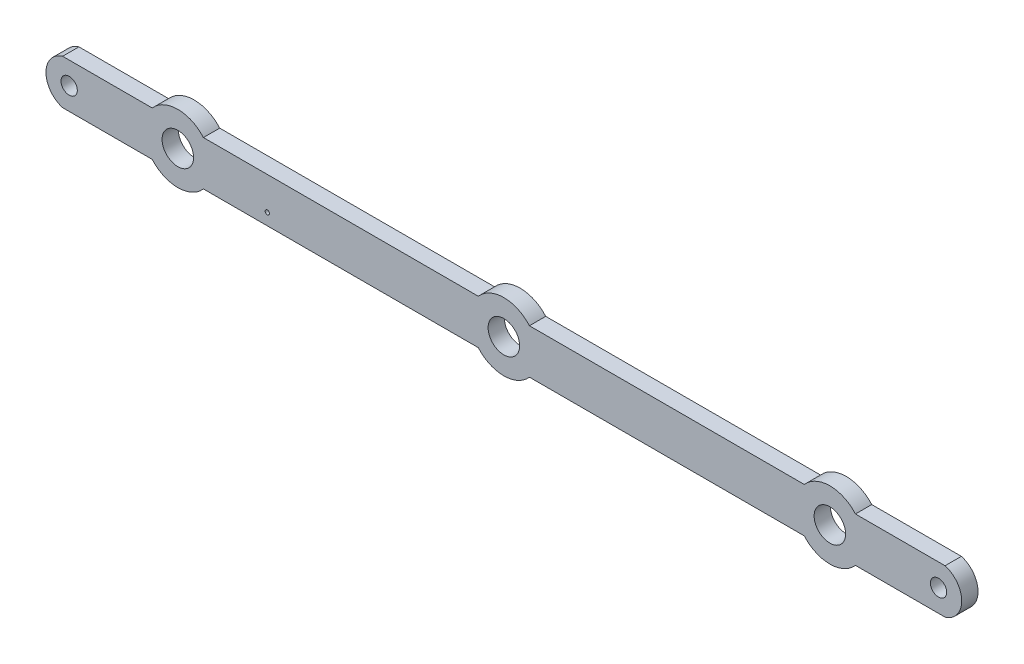
SolidWorks part; units mm, degrees
ref_plane "Front Plane" through (0, 0, 0) normal (0, 0, 1) x (1, 0, 0)
ref_plane "Top Plane" through (0, 0, 0) normal (0, 1, 0) x (1, 0, 0)
ref_plane "Right Plane" through (0, 0, 0) normal (1, 0, 0) x (0, 0, -1)
sketch "Sketch1" plane through (0, 0, 0) normal (0, 0, 1) x (1, 0, 0)
  line L0 (-80, 0) -> (-60, 0) construction
  line L5 (-31.34, 0) -> (-31.34, 4.2698) construction
  line L6 (-60, 0) -> (0, 0) construction
  line L7 (-81.2017, 4.0974) -> (-64.7063, 4.0974)
  line L8 (-81.2017, -4.0974) -> (-64.7063, -4.0974)
  line L9 (-55.2937, 4.0974) -> (-4.7063, 4.0974)
  line L10 (-55.2937, -4.0974) -> (-4.7063, -4.0974)
  line L11 (4.7063, 4.0974) -> (55.2937, 4.0974)
  line L12 (4.7063, -4.0974) -> (55.2937, -4.0974)
  line L13 (60, 0) -> (0, 0) construction
  line L14 (64.7063, 4.0974) -> (81.2017, 4.0974)
  line L15 (64.7063, -4.0974) -> (81.2017, -4.0974)
  line L16 (60, 0) -> (80, 0) construction
  circle A0 centre (-60, 0) radius 2.9
  circle A1 centre (0, 0) radius 2.9
  circle A2 centre (60, 0) radius 2.9
  circle A3 centre (80, 0) radius 1.5
  circle A4 centre (-80, 0) radius 1.5
  circle A5 centre (-43.5336, -1.9489) radius 0.3903
  arc A6 (-81.2017, 4.0974) -> (-81.2017, -4.0974) centre (-80, 0) ccw
  arc A7 (-64.7063, 4.0974) -> (-55.2937, 4.0974) centre (-60, 0) cw
  arc A8 (-64.7063, -4.0974) -> (-55.2937, -4.0974) centre (-60, 0) ccw
  arc A9 (4.7063, 4.0974) -> (-4.7063, 4.0974) centre (0, 0) ccw
  arc A10 (-4.7063, -4.0974) -> (4.7063, -4.0974) centre (0, 0) ccw
  arc A11 (64.7063, 4.0974) -> (55.2937, 4.0974) centre (60, 0) ccw
  arc A12 (55.2937, -4.0974) -> (64.7063, -4.0974) centre (60, 0) ccw
  arc A13 (81.2017, 4.0974) -> (81.2017, -4.0974) centre (80, 0) cw
  point P0 (0, 0)
  dimension "D1" = 5.8
  dimension "D2" = 3
  dimension "D8" = 4.27
  dimension "D10" = 6.24
  dimension "D5" = 160
  dimension "D3" = 20
  dimension "D4" = 28.66
  dimension "D6" = 60
extrude "Boss-Extrude1" add sketch "Sketch1" along normal blind 3
